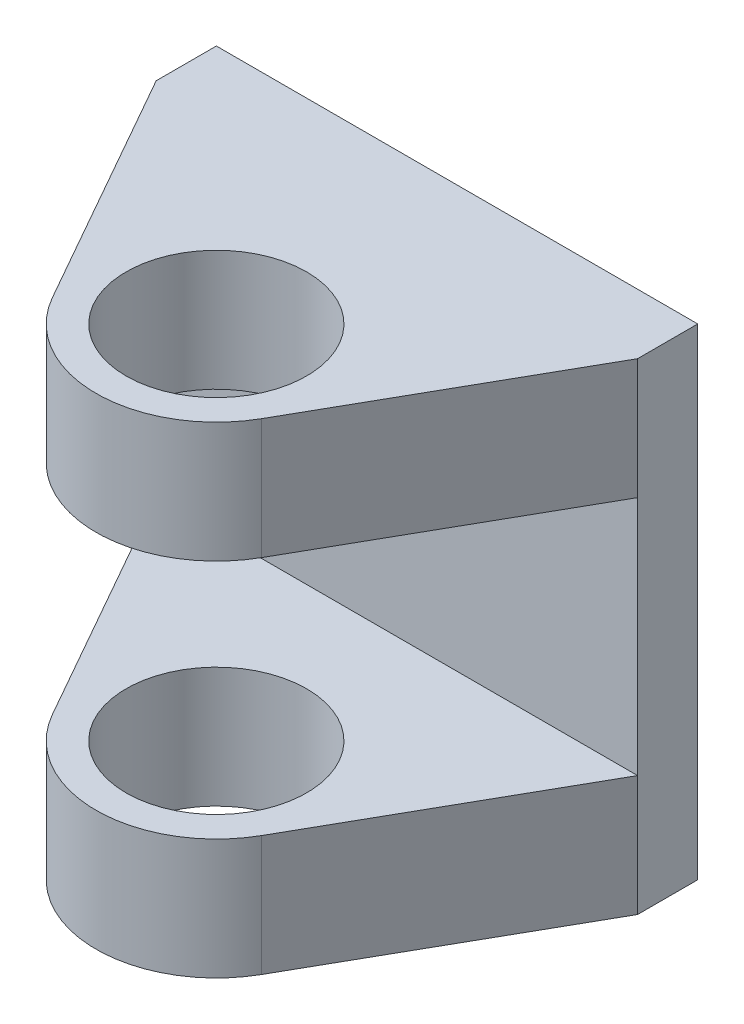
SolidWorks part; units mm, degrees
material "自定义塑料"
ref_plane "前视基准面" through (0, 0, 0) normal (0, 0, 1) x (1, 0, 0)
ref_plane "上视基准面" through (0, 0, 0) normal (0, 1, 0) x (1, 0, 0)
ref_plane "右视基准面" through (0, 0, 0) normal (1, 0, 0) x (0, 0, -1)
sketch "草图2" plane through (0, 0, 0) normal (0, 0, 1) x (1, 0, 0)
  line L1 (0, 0) -> (80, 0)
  line L2 (0, 0) -> (0, 80)
  line L3 (0, 80) -> (80, 80)
  line L4 (80, 0) -> (80, 80)
  dimension "D1" = 80
  dimension "D2" = 80
extrude "凸台-拉伸1" add sketch "草图2" along normal blind 10
sketch "草图3" plane through (0, 0, 0) normal (0, -1, 0) x (1, 0, 0)
  line L0 (0, 10) -> (22.6018, 49.8642)
  line L1 (0, 10) -> (80, 10)
  line L6 (57.3982, 49.8642) -> (80, 10)
  arc A0 (57.3982, 49.8642) -> (22.6018, 49.8642) centre (40, 40) ccw
  dimension "D2" = 40
extrude "凸台-拉伸2" add sketch "草图3" against normal blind 20
sketch "草图4" plane through (0, 80, 0) normal (0, 1, 0) x (1, 0, 0)
  line L0 (80, -10) -> (57.3982, -49.8642)
  line L1 (80, -10) -> (0, -10)
  line L6 (22.6018, -49.8642) -> (0, -10)
  arc A1 (22.6018, -49.8642) -> (57.3982, -49.8642) centre (40, -40) ccw
  dimension "D3" = 80
extrude "凸台-拉伸3" add sketch "草图4" against normal blind 20
sketch "草图5" plane through (0, 80, 0) normal (0, 1, 0) x (1, 0, 0)
  circle A0 centre (40, -40) radius 15
  dimension "D1" = 30
extrude "切除-拉伸1" cut sketch "草图5" against normal blind 80
